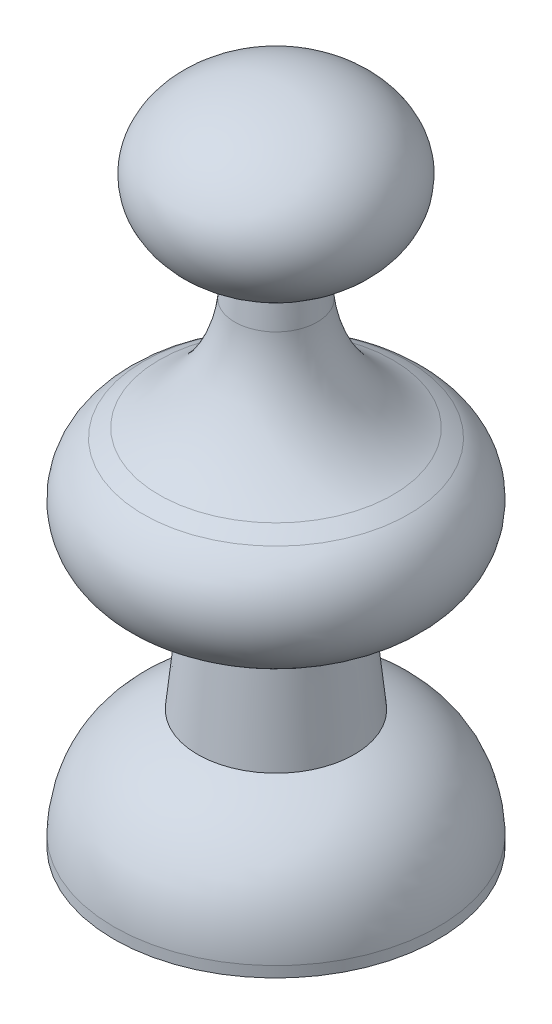
SolidWorks part; units mm, degrees
ref_plane "Front Plane" through (0, 0, 0) normal (0, 0, 1) x (1, 0, 0)
ref_plane "Top Plane" through (0, 0, 0) normal (0, 1, 0) x (1, 0, 0)
ref_plane "Right Plane" through (0, 0, 0) normal (1, 0, 0) x (0, 0, -1)
sketch "Sketch1" plane through (0, 0, 0) normal (0, 0, 1) x (1, 0, 0)
  line L0 (0, 0) -> (0, 46.0375) construction
  line L1 (0, 0) -> (-11.5, 0)
  line L2 (-5.5562, 7.6173) -> (-4.9017, 13.9035)
  line L3 (0, 26.9875) -> (-33.3364, 26.9875) construction
  line L4 (-11.5, 0) -> (-11.5, 46.0375) construction
  line L5 (-3.5771, 26.6242) -> (-2.6788, 35.251)
  line L6 (0, 46.0375) -> (0, 0)
  arc A0 (-3.5771, 26.6242) -> (-9.4101, 24.295) centre (0, 9.1974) ccw
  arc A1 (-9.4101, 24.295) -> (-8.6822, 16.399) centre (-7.0633, 20.5298) ccw
  arc A2 (-8.6822, 16.399) -> (-6.0312, 15.5356) centre (0, 38.5535) ccw
  arc A3 (-4.9017, 13.9035) -> (-6.0312, 15.5356) centre (-6.4175, 14.0613) ccw
  ellipse E0 centre (0, 40.4813) end of major axis (7.9375, 40.4813) minor radius 5.5562 (0, 46.0375) -> (-2.6788, 35.251) ccw
  spline S0 degree 2 poles (-11.5, 0) (-11.2207, 5.5448) (-5.5562, 7.6173) knots 0 0 0 1 1 1
  point P16 (-4.7625, 15.24)
  dimension "D10" = 1.524
  dimension "D1" = 46.0375
  dimension "D2" = 23
  dimension "D3" = 9.525
  dimension "D4" = 11.1125
  dimension "D5" = 7.6173
  dimension "D6" = 3.5818
  dimension "D7" = 10.5804
  dimension "D8" = 15.24
  dimension "D9" = 26.9875
  dimension "D11" = 15.875
  dimension "D12" = 11.1125
  dimension "D13" = 3.5771
revolve "Revolve2" add sketch "Sketch1" angle 360 about L6
fillet "Fillet1" radius 10.16 1 edges at (0, 26.6242, 3.5771)
sketch "Sketch2" plane through (0, 0, 0) normal (0, -1, 0) x (1, 0, 0)
  circle A1 centre (0, 0) radius 11.5
  circle A2 centre (0, 0) radius 11.5
  dimension "D1" = 0
extrude "Boss-Extrude1" add sketch "Sketch2" along normal blind 0.762 separate body
